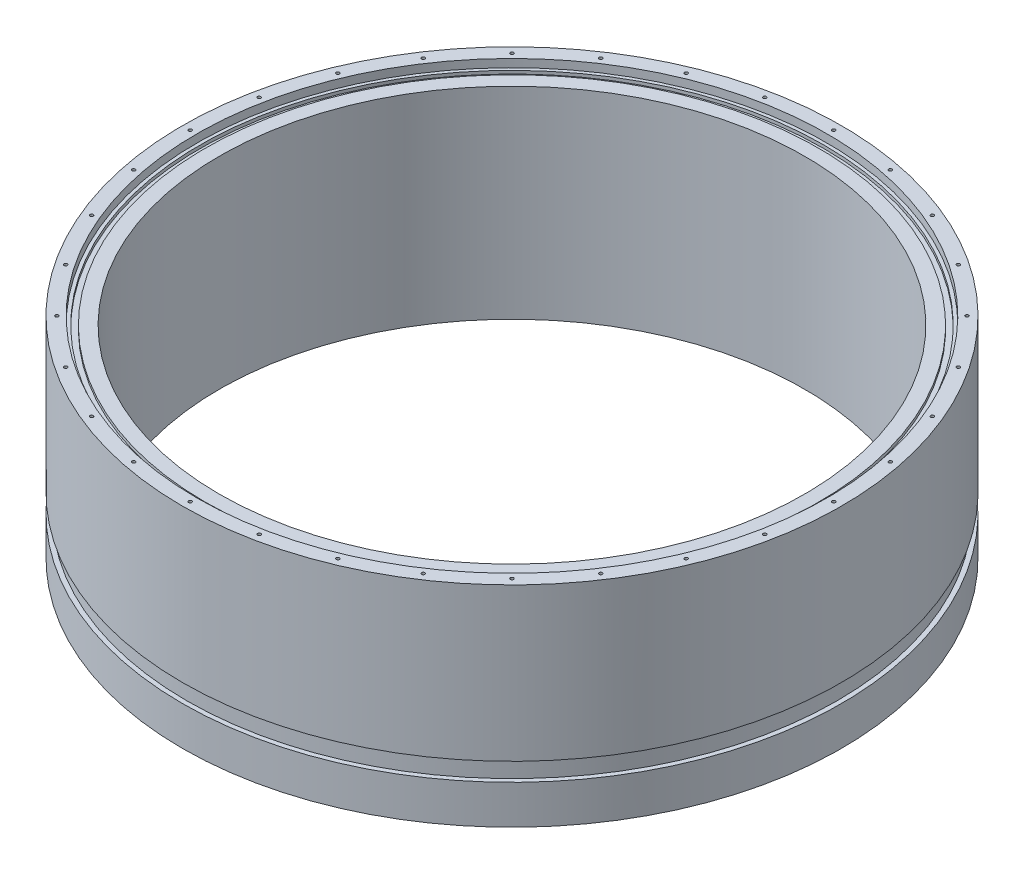
SolidWorks part; units mm, degrees
material "PVC Rigid"
ref_plane "Front" through (0, 0, 0) normal (0, 0, 1) x (1, 0, 0)
ref_plane "Top" through (0, 0, 0) normal (0, 1, 0) x (1, 0, 0)
ref_plane "Right" through (0, 0, 0) normal (1, 0, 0) x (0, 0, -1)
sketch "Sketch1" plane through (0, 0, 0) normal (0, 0, 1) x (1, 0, 0)
  line L0 (225.6, 74.685) -> (243, 74.685)
  line L1 (243, 74.685) -> (243, 80.885)
  line L2 (243, 80.885) -> (254, 80.885)
  line L3 (254, 80.885) -> (254, -80.885)
  line L4 (254, -80.885) -> (225.6, -80.885)
  line L5 (225.6, -80.885) -> (225.6, 74.685)
  line L6 (0, 80.885) -> (0, -80.885) construction
  line L7 (0, 0) -> (225.6, 0) construction
  dimension "D1" = 508
  dimension "D2" = 11
  dimension "D3" = 28.4
  dimension "D4" = 6.2
  dimension "D5" = 161.77
  dimension "D6" = 225.6
  dimension "D7" = 155.57
revolve "Revolve1" add sketch "Sketch1" angle 360 about L6
sketch "Sketch2" plane through (0, 0, 0) normal (0, 0, 1) x (1, 0, 0)
  line L0 (0, 80.885) -> (0, -80.885) construction
  line L1 (254, 80.885) -> (-254, 80.885) construction
  line L2 (-254, -80.885) -> (254, -80.885) construction
  line L3 (240.5, 72.272) -> (240.5, -77.587) construction
  line L4 (236.3344, 74.685) -> (240.5, 74.685)
  line L5 (236.3344, 74.685) -> (236.3344, 72.272)
  line L6 (236.3344, 72.272) -> (240.5, 72.272)
  line L7 (240.5, 74.685) -> (240.5, 72.272)
  line L8 (225.6, 74.685) -> (-225.6, 74.685) construction
  line L9 (225.6, 74.685) -> (-225.6, 74.685) construction
  line L10 (254, -80.885) -> (254, 80.885) construction
  line L12 (236.3344, -78.472) -> (240.5, -78.472) construction
  line L13 (236.3344, -78.472) -> (236.3344, -80.885) construction
  line L14 (236.3344, -80.885) -> (240.5, -80.885) construction
  line L15 (240.5, -78.472) -> (240.5, -80.885) construction
  dimension "D1" = 13.5
  dimension "D2" = 2.413
  dimension "D3" = 4.1656
revolve "Cut-Revolve1" cut sketch "Sketch2" angle 360 about L0
hole_wizard "M3x0.5 Tapped Hole1" positions "Sketch3" profile "Sketch4" tap size "M3x0.5" standard "ANSI Metric"
sketch "Sketch3" plane through (0, 80.885, 0) normal (0, 1, 0) x (1, 0, 0)
  point P0 (248, 0)
  dimension "D1" = 248
sketch "Sketch4" plane through (248, 80.885, 0) normal (1, 0, 0) x (0, 0, 1)
  line L0 (0, 0) -> (0, 10.2511)
  line L1 (0, 10.2511) -> (1.25, 9.5)
  line L2 (1.25, 9.5) -> (1.25, 0)
  line L5 (1.25, 0) -> (0, 0)
  line L10 (0, 10.2511) -> (-1.25, 9.5) construction
  line L11 (0, -6.35) -> (0, 107.95) construction
  dimension "Tap Drill Dia." = 2.5
  dimension "Tap Drill Depth" = 9.5
  dimension "Drill Angle" = 118
cosmetic thread "Hole Thread1" parameters "D1"=8, "D2"=3
pattern_circular "CirPattern1" count 32 over 360 about axis through (0, 0, 0) along (0, 1, 0) of "M3x0.5 Tapped Hole1"
mirror "Mirror1" about plane through (0, 0, 0) normal (0, 1, 0) of "CirPattern1", "M3x0.5 Tapped Hole1"
hole_wizard "Ø5.0mm Dowel Hole1" positions "Sketch5" profile "Sketch6" hole size "Ø5.0" standard "ANSI Metric"
sketch "Sketch5" plane through (0, -80.885, 0) normal (0, -1, 0) x (-1, 0, 0)
  line L2 (0, 0) -> (0, 204.5498) construction
  line L3 (-24.2102, 245.8106) -> (0, 0) construction
  line L4 (0, 0) -> (24.9245, -253.0623) construction
  circle A1 centre (0, 0) radius 247
  point P6 (-24.2102, 245.8106)
  point P8 (24.2102, -245.8106)
  dimension "D2" = 494
  dimension "D1" = 5.625
sketch "Sketch6" plane through (-24.2102, -80.885, 245.8106) normal (1, 0, 0) x (0, 0, -1)
  line L0 (0, 0) -> (0, 21.0172)
  line L1 (0, 21.0172) -> (2.525, 19.5)
  line L2 (2.525, 19.5) -> (2.525, 0)
  line L5 (2.525, 0) -> (0, 0)
  line L10 (0, 21.0172) -> (-2.525, 19.5) construction
  line L11 (0, -6.35) -> (0, 107.95) construction
  dimension "Hole Dia." = 5.05
  dimension "Hole Depth" = 19.5
  dimension "Drill Angle" = 118
sketch "Sketch7" plane through (0, 0, 0) normal (0, 0, 1) x (1, 0, 0)
  line L0 (254, -80.885) -> (254, 80.885) construction
  line L1 (254, -36.885) -> (250.5, -36.885)
  line L2 (254, -36.885) -> (254, -50.885)
  line L3 (254, -50.885) -> (250.5, -50.885)
  line L4 (250.5, -36.885) -> (250.5, -50.885)
  line L5 (-254, -80.885) -> (254, -80.885) construction
  line L6 (0, 0) -> (0, 101.0438) construction
  dimension "D1" = 250.5
  dimension "D2" = 14
  dimension "D3" = 30
revolve "groove" cut sketch "Sketch7" angle 360 about L6
